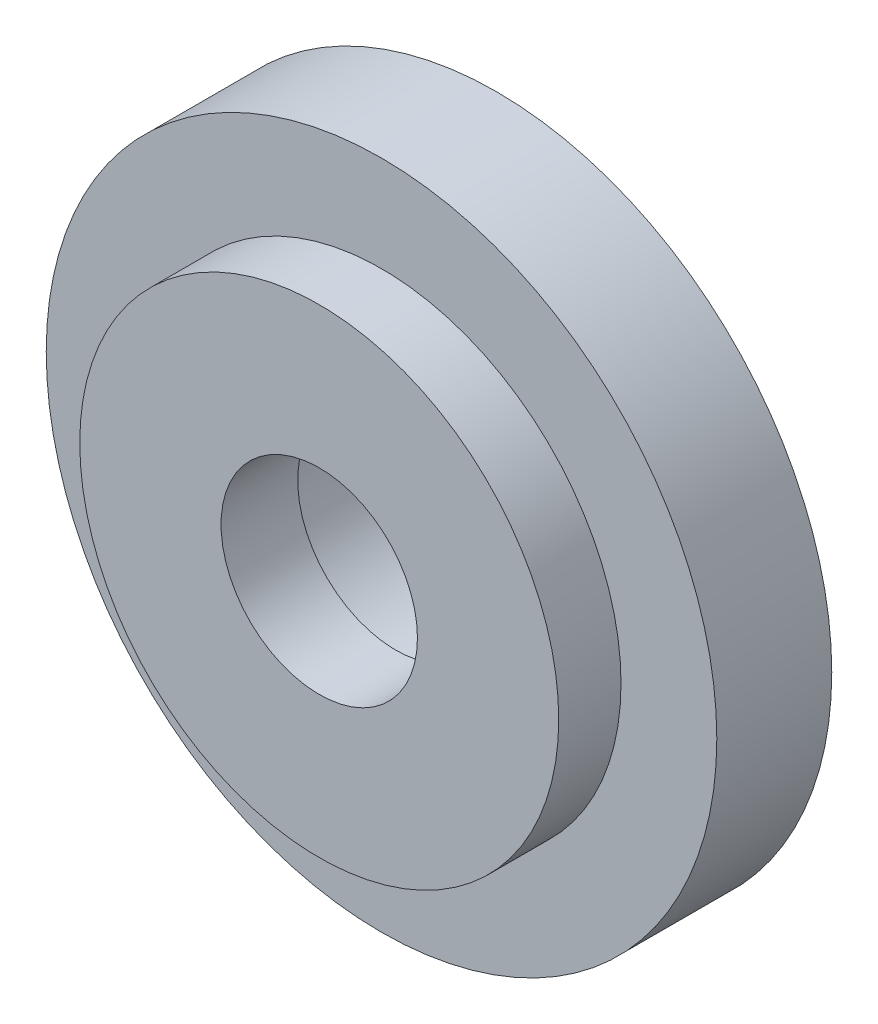
SolidWorks part; units mm, degrees
ref_plane "Front Plane" through (0, 0, 0) normal (0, 0, 1) x (1, 0, 0)
ref_plane "Top Plane" through (0, 0, 0) normal (0, 1, 0) x (1, 0, 0)
ref_plane "Right Plane" through (0, 0, 0) normal (1, 0, 0) x (0, 0, -1)
sketch "Sketch1" plane through (0, 0, 0) normal (0, 0, 1) x (1, 0, 0)
  circle A1 centre (0, 0) radius 12.7
  dimension "D2" = 25.4
extrude "Boss-Extrude1" add sketch "Sketch1" along normal blind 12.7
ref_plane "Plane1" through (0, 0, 6.35) normal (0, 0, 1) x (1, 0, 0)
sketch "Sketch2" plane through (0, 0, 6.35) normal (0, 0, 1) x (1, 0, 0)
  circle A2 centre (0, 0) radius 17.78
  dimension "D1" = 35.56
extrude "Boss-Extrude2" add sketch "Sketch2" along normal mid plane 6.096
sketch "Sketch9" plane through (0, 0, 6.35) normal (0, 0, 1) x (1, 0, 0)
  circle A0 centre (0, 0) radius 6.477
  dimension "D1" = 12.954
extrude "Cut-Extrude5" cut sketch "Sketch9" against normal mid plane 4.572
sketch "Sketch10" plane through (0, 0, 0) normal (0, 0, -1) x (-1, 0, 0)
  circle A0 centre (0, 0) radius 6.731
  dimension "D1" = 13.462
extrude "Cut-Extrude6" cut sketch "Sketch10" against normal up to surface (4.064 mm away) up to face at (6.477, 0, 4.064)
sketch "Sketch11" plane through (0, 0, 12.7) normal (0, 0, 1) x (1, 0, 0)
  circle A0 centre (0, 0) radius 5.207
  dimension "D1" = 10.414
extrude "Cut-Extrude7" cut sketch "Sketch11" against normal through all
